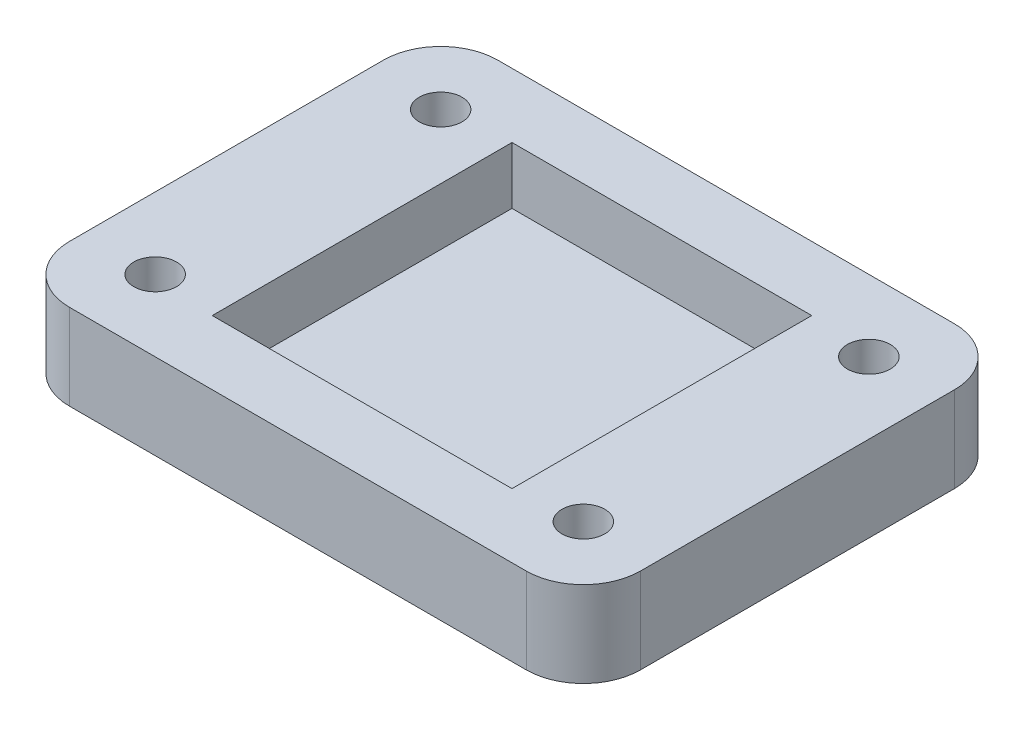
SolidWorks part; units mm, degrees
ref_plane "Front" through (0, 0, 0) normal (0, 0, 1) x (1, 0, 0)
ref_plane "Top" through (0, 0, 0) normal (0, 1, 0) x (1, 0, 0)
ref_plane "Right" through (0, 0, 0) normal (1, 0, 0) x (0, 0, -1)
sketch "Sketch1" plane through (0, 0, 0) normal (0, 1, 0) x (1, 0, 0)
  line L1 (0, 0) -> (40, 0)
  line L2 (0, 0) -> (0, 30)
  line L3 (0, 30) -> (40, 30)
  line L4 (40, 0) -> (40, 30)
  dimension "D1" = 40
  dimension "D2" = 30
extrude "Boss-Extrude1" add sketch "Sketch1" along normal blind 6
sketch "Sketch2" plane through (0, 6, 0) normal (0, 1, 0) x (1, 0, 0)
  line L0 (20, 30) -> (20, 0) construction
  line L1 (40, 30) -> (0, 30) construction
  line L2 (0, 0) -> (40, 0) construction
  line L3 (0, 15) -> (40, 15) construction
  line L4 (0, 30) -> (0, 0) construction
  line L5 (40, 0) -> (40, 30) construction
  circle A0 centre (5, 5) radius 1.5
  circle A1 centre (5, 25) radius 1.5
  circle A2 centre (35, 5) radius 1.5
  circle A3 centre (35, 25) radius 1.5
  dimension "D1" = 3
  dimension "D2" = 5
  dimension "D3" = 5
extrude "Cut-Extrude1" cut sketch "Sketch2" against normal up to surface (6 mm away) up to face at (20, 0, -15)
fillet "Fillet1" radius 4 4 edges at (0, 3, -30) (40, 3, -30) (40, 3, 0) (0, 3, 0)
sketch "Sketch3" plane through (0, 6, 0) normal (0, 1, 0) x (1, 0, 0)
  line L0 (4, 0) -> (36, 0) construction
  line L1 (9.5, 4.5) -> (30.5, 4.5)
  line L2 (9.5, 4.5) -> (9.5, 25.5)
  line L3 (9.5, 25.5) -> (30.5, 25.5)
  line L4 (30.5, 4.5) -> (30.5, 25.5)
  line L5 (0, 26) -> (0, 4) construction
  point P4 (20, 4.5)
  point P7 (20, 0)
  point P8 (9.5, 15)
  point P11 (0, 15)
  dimension "D1" = 21
  dimension "D2" = 21
extrude "Cut-Extrude2" cut sketch "Sketch3" against normal blind 4
